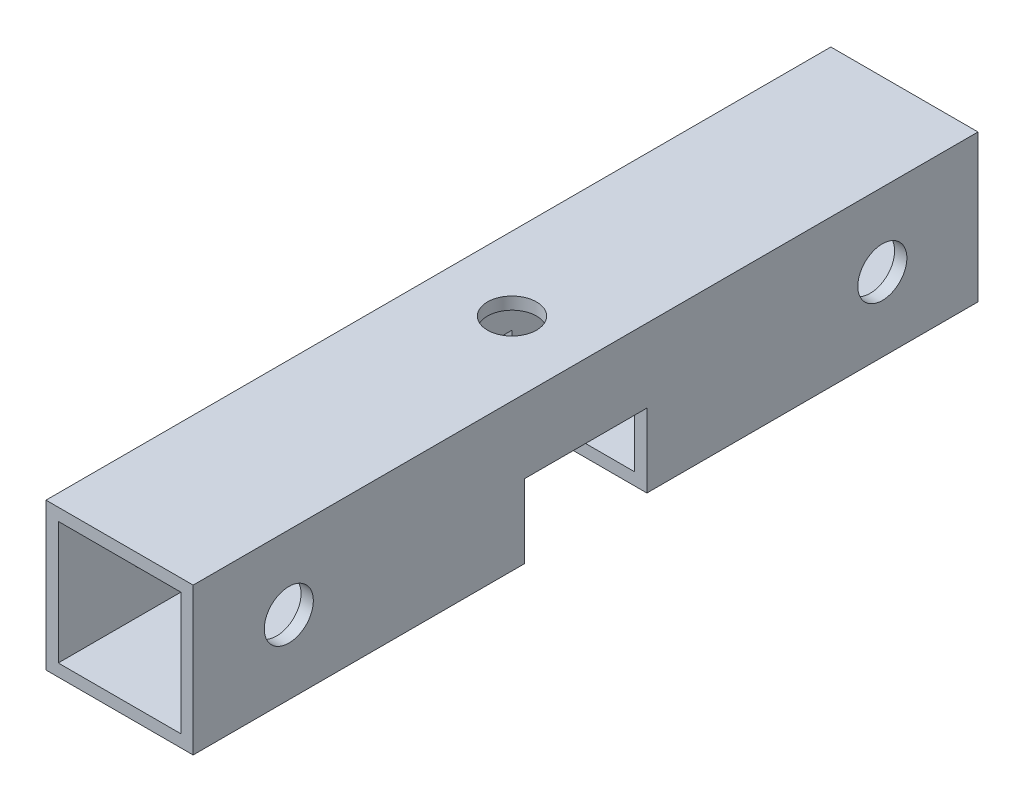
SolidWorks part; units mm, degrees
material "6061-T6 (SS)"
ref_plane "Front Plane" through (0, 0, 0) normal (0, 0, 1) x (1, 0, 0)
ref_plane "Top Plane" through (0, 0, 0) normal (0, 1, 0) x (1, 0, 0)
ref_plane "Right Plane" through (0, 0, 0) normal (1, 0, 0) x (0, 0, -1)
sketch "Sketch1" plane through (0, 0, 0) normal (0, 0, 1) x (1, 0, 0)
  line L0 (-7.9375, 7.9375) -> (7.9375, 7.9375)
  line L1 (-9.525, -9.525) -> (9.525, -9.525)
  line L2 (-9.525, -9.525) -> (-9.525, 9.525)
  line L3 (-9.525, 9.525) -> (9.525, 9.525)
  line L4 (9.525, -9.525) -> (9.525, 9.525)
  line L5 (-9.525, -9.525) -> (9.525, 9.525) construction
  line L6 (-9.525, 9.525) -> (9.525, -9.525) construction
  line L7 (7.9375, -7.9375) -> (7.9375, 7.9375)
  line L8 (-7.9375, -7.9375) -> (7.9375, -7.9375)
  line L9 (-7.9375, -7.9375) -> (-7.9375, 7.9375)
  point P0 (0, 0)
  dimension "D1" = 19.05
  dimension "D2" = 1.5875
extrude "Boss-Extrude1" add sketch "Sketch1" along normal blind 101.6
sketch "Sketch2" plane through (0, 9.525, 0) normal (0, 1, 0) x (1, 0, 0)
  line L0 (9.525, -50.8) -> (0, -50.8) construction
  line L1 (9.525, -101.6) -> (9.525, 0) construction
  line L2 (9.525, 0) -> (-9.525, 0) construction
  line L3 (0, 0) -> (0, -50.8) construction
  circle A0 centre (0, -50.8) radius 3.175
  dimension "D1" = 6.35
extrude "Cut-Extrude1" cut sketch "Sketch2" against normal through all
sketch "Sketch3" plane through (9.525, 0, 0) normal (1, 0, 0) x (0, 0, -1)
  line L0 (-50.8, -9.525) -> (-50.8, -4.7625) construction
  line L1 (-101.6, -9.525) -> (0, -9.525) construction
  line L2 (-101.6, 0) -> (-89.2175, 0) construction
  line L3 (-42.8625, 0) -> (-58.7375, 0)
  line L4 (-42.8625, 0) -> (-42.8625, -9.525)
  line L5 (-42.8625, -9.525) -> (-58.7375, -9.525)
  line L6 (-58.7375, 0) -> (-58.7375, -9.525)
  line L7 (-42.8625, 0) -> (-58.7375, -9.525) construction
  line L8 (-42.8625, -9.525) -> (-58.7375, 0) construction
  line L9 (-101.6, -9.525) -> (-101.6, 9.525) construction
  circle A0 centre (-89.2175, 0) radius 3.175
  circle A1 centre (-12.3825, 0) radius 3.175
  dimension "D3" = 6.35
  dimension "D4" = 30.48
  dimension "D1" = 9.525
  dimension "D2" = 15.875
extrude "Cut-Extrude2" cut sketch "Sketch3" against normal through all
